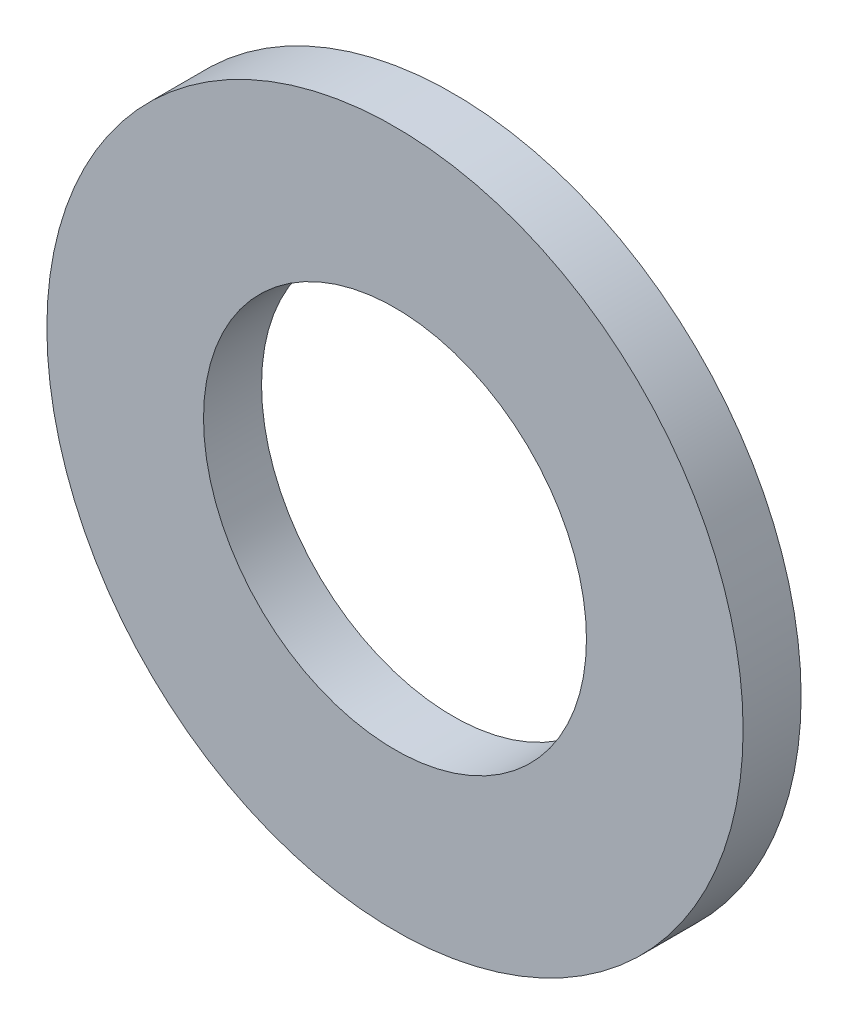
SolidWorks part; units mm, degrees
material "Nylon 101"
ref_plane "Front Plane" through (0, 0, 0) normal (0, 0, 1) x (1, 0, 0)
ref_plane "Top Plane" through (0, 0, 0) normal (0, 1, 0) x (1, 0, 0)
ref_plane "Right Plane" through (0, 0, 0) normal (1, 0, 0) x (0, 0, -1)
sketch "Sketch1" plane through (0, 0, 0) normal (0, 0, 1) x (1, 0, 0)
  circle A0 centre (0, 0) radius 9.525
  circle A1 centre (0, 0) radius 5.2387
  dimension "D1" = 19.05
  dimension "D2" = 10.4775
extrude "Boss-Extrude1" add sketch "Sketch1" along normal mid plane 1.5875
equation "\"D1@Boss-Extrude1\"=0.0625in+0.45mm/2"
